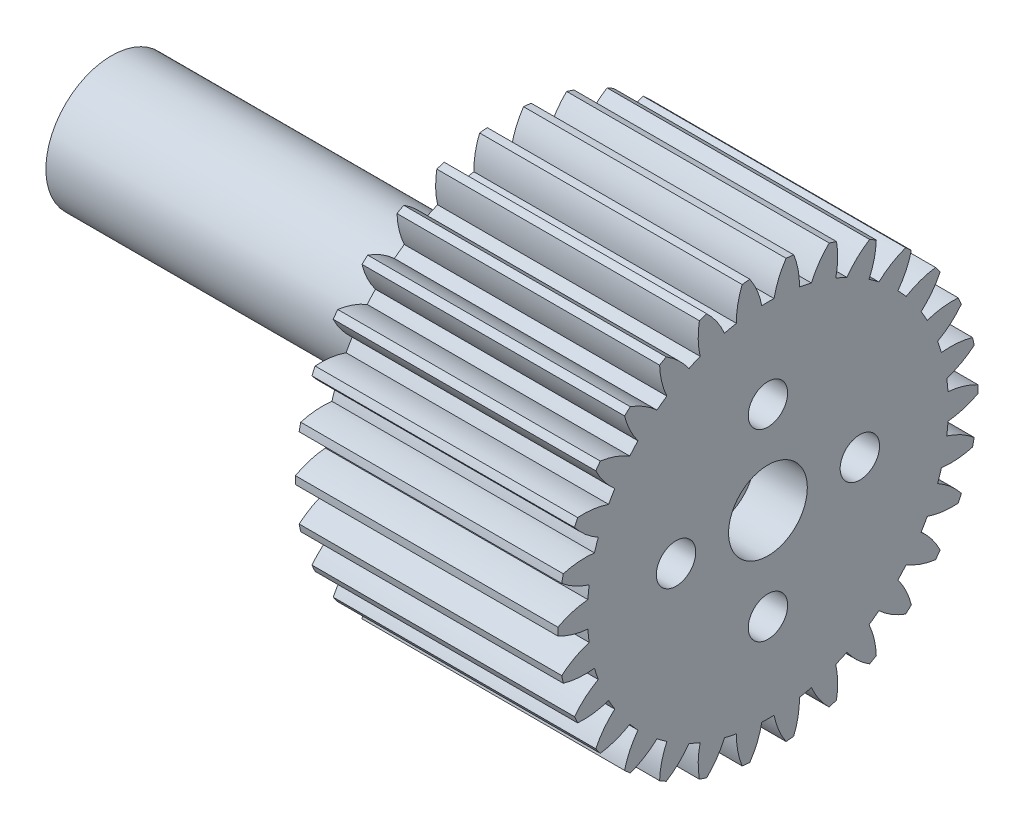
SolidWorks part; units mm, degrees
ref_plane "Plane1" through (0, 0, 0) normal (0, 0, 1) x (1, 0, 0)
ref_plane "Plane2" through (0, 0, 0) normal (0, 1, 0) x (1, 0, 0)
ref_plane "Plane3" through (0, 0, 0) normal (1, 0, 0) x (0, 0, -1)
sketch "HoldingSke" plane through (0, 0, 0) normal (0, 1, 0) x (1, 0, 0)
  line L0 (0, 0) -> (0.866, -0.5)
  line L1 (-15, 0) -> (100, 0) construction
  line L2 (0, 0) -> (-2.1039, 2.3779)
  line L3 (0, 0) -> (-11.863, 4.5341)
  line L4 (0, 0) -> (7.479, 4.318)
  line L5 (0, 0) -> (-46.8476, -17.4728)
  line L6 (0, 0) -> (-16.5793, -11.1861)
  line L7 (-2.1039, 2.3779) -> (8.6586, 51.2059)
  line L8 (-76.2, 54.61) -> (-76.1, 54.61)
  line L9 (-71.009, 38.7566) -> (-53.1078, 45.2721)
  line L10 (-76.2, 71.12) -> (104.1128, 71.12)
  line L11 (0, 0) -> (-20, 0)
  line L12 (-76.2, 101.6) -> (-76.162, 101.6)
  line L13 (24.9733, 27.94) -> (52.9518, 28.4284)
  line L14 (24.9733, 27.94) -> (24.9743, 27.94)
  line L15 (24.9733, 27.94) -> (100.4006, 29.5858)
  line L16 (-63.627, -1) -> (-12.827, -1)
  circle A0 centre (0, 0) radius 0.4
  circle A1 centre (0, 0) radius 13.749
  circle A2 centre (0, 0) radius 37.5
  circle A3 centre (0, 0) radius 0.4
  dimension "MHD" = 27.498
  dimension "Hub_dia" = 75
  dimension "Bore" = 0.8
  dimension "MBD" = 0.8
  dimension "Num_teeth" = 30
  dimension "Pitch" = 1
  dimension "Overall_len" = 50
  dimension "Show_teeth" = 30
  dimension "Thickness" = 20
  dimension "OAL" = 50.0001
  dimension "T_dim" = 0.1
  dimension "Ap" = 20
  dimension "H" = 19.05
  dimension "Pitch_radius" = 180.3128
  dimension "Width" = 20
  dimension "Backlash" = 0.038
  dimension "Addendum_fac" = 1
  dimension "Dedendum_fac" = 1.25
  dimension "Clearance_fac" = 0.25
  dimension "Dedendum_add" = 0.001
  dimension "Module" = 1
sketch "BasProSke" plane through (0, 0, 0) normal (0, 1, 0) x (1, 0, 0)
  line L0 (-10, 0) -> (60, 0) construction
  line L1 (0, 0) -> (0, 16)
  line L2 (0, 0) -> (20, 0)
  line L3 (20, 0) -> (20, 16)
  line L4 (20, 16) -> (0, 16)
  dimension "Thickness" = 20
  dimension "Diameter" = 32
revolve "Base-Revolve" add sketch "BasProSke" angle 360 about L0
sketch "TooCutSke" plane through (0, 0, 0) normal (1, 0, 0) x (0, 0, -1)
  line L1 (0, 0) -> (0, 107) construction
  line L2 (0, 0) -> (-0.8515, 14.9758) construction
  line L3 (0, 0) -> (-3.1323, 29.8014) construction
  line L4 (-0.8515, 14.9758) -> (-1.5661, 14.9007) construction
  arc A0 (0.4664, 13.7411) -> (-0.4664, 13.7411) centre (0, 0) ccw
  arc A1 (1.3975, 15.9644) -> (-1.3975, 15.9644) centre (0, 0) ccw
  circle A2 centre (0, 0) radius 15 construction
  circle A3 centre (0, 0) radius 14.0954 construction
  arc A4 (-0.4664, 13.7411) -> (-1.3975, 15.9644) centre (-6.3534, 12.5823) ccw
  arc A5 (1.3975, 15.9644) -> (0.4664, 13.7411) centre (6.3534, 12.5823) ccw
  dimension "Root_dia" = 27.498
  dimension "Overcut_dia" = 32.0508
  dimension "Pitch_dia" = 30
  dimension "Base_dia" = 28.1908
  dimension "Flank_rad" = 6
  dimension "Half_ang" = 6
  dimension "Half_CT" = 0.7185
extrude "ToothCut" cut sketch "TooCutSke" along normal through all
fillet "Breaks" [suppressed] radius 0.02
fillet "RootFillets" [suppressed] radius 0.251
pattern_circular "TeethCuts" count 30 every 12 about axis through (-10, 0, 0) along (1, 0, 0) of "ToothCut", "RootFillets", "Breaks"
sketch "HubNeaOneSke" plane through (0, 0, 0) normal (-1, 0, 0) x (0, 0, 1)
  circle A0 centre (0, 0) radius 13.749
  dimension "Diameter" = 27.498
extrude "HubNearOne" [suppressed] add sketch "HubNeaOneSke" along normal blind 30.0001
sketch "HubNeaBotSke" plane through (0, 0, 0) normal (-1, 0, 0) x (0, 0, 1)
  circle A0 centre (0, 0) radius 13.749
  dimension "Diameter" = 27.498
extrude "HubNearBoth" [suppressed] add sketch "HubNeaBotSke" along normal blind 15
ref_plane "FarPln" through (20, 0, 0) normal (1, 0, 0) x (0, 0, -1)
sketch "HubFarSke" plane through (20, 0, 0) normal (1, 0, 0) x (0, 0, -1)
  circle A0 centre (0, 0) radius 13.749
  dimension "Diameter" = 27.498
extrude "HubFar" [suppressed] add sketch "HubFarSke" along normal blind 15
sketch "BorSke" plane through (0, 0, 0) normal (1, 0, 0) x (0, 0, -1)
  circle A0 centre (0, 0) radius 0.4
  dimension "Diameter" = 0.8
extrude "Bore" cut sketch "BorSke" along normal mid plane 100.0001
sketch "KeySke" plane through (0, 0, 0) normal (1, 0, 0) x (0, 0, -1)
  line L0 (-0.05, 0) -> (-0.05, 0.5)
  line L1 (-0.05, 0.5) -> (0.05, 0.5)
  line L2 (0.05, 0.5) -> (0.05, 0)
  line L3 (0, 0) -> (0, 34) construction
  line L4 (-0.05, 0) -> (0.05, 0)
  dimension "Offset" = 0.5
  dimension "Width" = 0.1
extrude "Keyway" [suppressed] cut sketch "KeySke" along normal mid plane 100.0001
pattern_circular "Keyway2" [suppressed] count 2 every 90 about axis through (-10, 0, 0) along (1, 0, 0)
sketch "草图1" plane through (20, 0, 0) normal (1, 0, 0) x (0, 0, -1)
  line L0 (0, 0) -> (7, 0)
  line L1 (0, 0) -> (-7, 0)
  line L2 (0, 0) -> (0, 7)
  line L3 (0, 0) -> (0, -7)
  circle A0 centre (0, 0) radius 3
sketch "草图2" plane through (20, 0, 0) normal (1, 0, 0) x (0, 0, -1)
  circle A0 centre (0, 0) radius 5
extrude "凸台-拉伸1" add sketch "草图2" against normal blind 50
sketch "草图3" plane through (20, 0, 0) normal (1, 0, 0) x (0, 0, -1)
  circle A0 centre (0, 7) radius 1.5
  circle A1 centre (7, 0) radius 1.5
  circle A2 centre (0, -7) radius 1.5
  circle A3 centre (-7, 0) radius 1.5
extrude "切除-拉伸1" cut sketch "草图3" against normal up to next
extrude "切除-拉伸2" cut sketch "草图1" against normal blind 4 contours L2 A0 L1 | L0 A0 L2 | L1 A0 L3 | L3 A0 L0
hole_wizard "M6 螺纹孔1" positions "草图5" profile "草图6" tap size "M6" standard "GB"
sketch "草图5" plane through (-30, 0, 0) normal (-1, 0, 0) x (0, 0, 1)
  point P0 (0, 0)
sketch "草图6" plane through (-30, 0, 0) normal (0, 1, 0) x (0, 0, 1)
  line L0 (0, 0) -> (0, 16.5022)
  line L1 (0, 16.5022) -> (2.5, 15)
  line L2 (2.5, 15) -> (2.5, 0)
  line L5 (2.5, 0) -> (0, 0)
  line L10 (0, 16.5022) -> (-2.5, 15) construction
  line L11 (0, -6.35) -> (0, 107.95) construction
  dimension "螺纹孔钻头直径" = 5
  dimension "螺纹孔钻头深度" = 15
  dimension "导头角度" = 118
cosmetic thread "孔螺蚊线1" parameters "D1"=12, "D2"=6
equation "' \"Module@HoldingSke\" = 6.35"
equation "' \"Num_teeth@HoldingSke\" = 12"
equation "' \"Ap@HoldingSke\" =  20"
equation "' \"Ap@HoldingSke\" = 20"
equation "' \"Width@HoldingSke\" = 0.5 * 25.4"
equation "' \"Hub_dia@HoldingSke\"= 1 * 25.4"
equation "' \"Hub_dia@HoldingSke\" = 1 * 25.4"
equation "' \"Overall_len@HoldingSke\" = 1.0 * 25.4"
equation "' \"Bore@HoldingSke\" = 0.75 * 25.4"
equation "' \"T_dim@HoldingSke\" = 0.1 * 25.4"
equation "' \"Width@KeySke\" = 0.25 * 25.4"
equation "' \"Show_teeth@HoldingSke\" = 13"
equation "' \"Backlash@HoldingSke\" = 0.009 * 25.4"
equation "' \"Addendum_fac@HoldingSke\" = 1.0"
equation "' \"Dedendum_fac@HoldingSke\" = 1.25"
equation "' \"Dedendum_add@HoldingSke\" = 0.00005 * 25.4"
equation "' \"Clearance_fac@HoldingSke\" = 0.25"
equation "\"Pitch@HoldingSke\" = 1 / \"Module@HoldingSke\""
equation "\"Overcut_dia@TooCutSke\" = (\"Num_teeth@HoldingSke\" + 2 * \"Addendum_fac@HoldingSke\") / \"Pitch@HoldingSke\" + 0.002 * 25.4"
equation "\"Pitch_dia@TooCutSke\" = \"Num_teeth@HoldingSke\" / \"Pitch@HoldingSke\""
equation "\"Base_dia@TooCutSke\" = \"Num_teeth@HoldingSke\" / \"Pitch@HoldingSke\" * cos((\"Ap@HoldingSke\"  * 3.14159265 / 180))"
equation "\"Root_dia@TooCutSke\" = (\"Num_teeth@HoldingSke\" + 2) / \"Pitch@HoldingSke\" - 2 * (\"Addendum_fac@HoldingSke\" + \"Dedendum_fac@HoldingSke\") / \"Pitch@HoldingSke\" - \"Dedendum_add@HoldingSke\" * 2"
equation "\"Half_ang@TooCutSke\" = 180 / \"Num_teeth@HoldingSke\""
equation "\"Half_CT@TooCutSke\" = \"Num_teeth@HoldingSke\" / \"Pitch@HoldingSke\" * sin((3.14159265 / 2 / \"Num_teeth@HoldingSke\")) / 2 - 7 * \"Backlash@HoldingSke\" / 4"
equation "\"Flank_rad@TooCutSke\" = \"Num_teeth@HoldingSke\" / \"Pitch@HoldingSke\" / 5"
equation "\"Radius@RootFillets\" = \"Clearance_fac@HoldingSke\" / \"Pitch@HoldingSke\" + \"Dedendum_add@HoldingSke\""
equation "\"Break_rad@Breaks\" = 0.02 / \"Pitch@HoldingSke\""
equation "\"Thickness@HoldingSke\" = \"Width@HoldingSke\""
equation "\"OAL@HoldingSke\" = \"Thickness@HoldingSke\""
equation "\"MHD@HoldingSke\" = (\"Num_teeth@HoldingSke\" + 2) / \"Pitch@HoldingSke\" - 2 * (\"Addendum_fac@HoldingSke\" + \"Dedendum_fac@HoldingSke\")  / \"Pitch@HoldingSke\" - \"Dedendum_add@HoldingSke\" * 2"
equation "\"MBD@HoldingSke\" = (\"Num_teeth@HoldingSke\" + 2) / \"Pitch@HoldingSke\" - 2 * (\"Addendum_fac@HoldingSke\" + \"Dedendum_fac@HoldingSke\")  / \"Pitch@HoldingSke\" - \"Dedendum_add@HoldingSke\" * 2 - 0.002 * 25.4"
equation "\"MHD@HoldingSke\" = ((sgn( \"MHD@HoldingSke\" - \"Hub_dia@HoldingSke\" )-1)*( \"MHD@HoldingSke\" - \"Hub_dia@HoldingSke\" ))/-2+ \"Hub_dia@HoldingSke\""
equation "\"MBD@HoldingSke\" = ((sgn( \"MBD@HoldingSke\" - \"Bore@HoldingSke\" )-1)*( \"MBD@HoldingSke\" - \"Bore@HoldingSke\" ))/-2+ \"Bore@HoldingSke\""
equation "\"OAL@HoldingSke\" = ((sgn( \"OAL@HoldingSke\" - \"Overall_len@HoldingSke\" )+1)*( \"OAL@HoldingSke\" - \"Overall_len@HoldingSke\" ))/2 + \"Overall_len@HoldingSke\" + 0.000002 * 25.4"
equation "\"Num_teeth@TeethCuts\" = int( \"Show_teeth@HoldingSke\" ) + 1"
equation "\"Num_teeth@TeethCuts\" = ((sgn( \"Num_teeth@TeethCuts\" - \"Num_teeth@HoldingSke\" )-1)*( \"Num_teeth@TeethCuts\" - \"Num_teeth@HoldingSke\" ))/-2+ \"Num_teeth@HoldingSke\""
equation "\"Num_teeth@TeethCuts\" = ((sgn( \"Num_teeth@TeethCuts\" - 2.0)+1)*( \"Num_teeth@TeethCuts\" - 2.0))/2 +2.0"
equation "\"Angle@TeethCuts\" = 360.0 / \"Num_teeth@HoldingSke\""
equation "\"Diameter@BasProSke\" = (\"Num_teeth@HoldingSke\" + 2 * \"Addendum_fac@HoldingSke\") / \"Pitch@HoldingSke\""
equation "\"Thickness@BasProSke\"  = \"Thickness@HoldingSke\""
equation "' \"Fillet_rad@BasProSke\" =  \"Thickness@HoldingSke\" * 0.05"
equation "' \"Fillet_rad@BasProSke\" = \"Thickness@HoldingSke\" * 0.05"
equation "\"MHD@HoldingSke\" = ((sgn( \"MHD@HoldingSke\" - \"Root_dia@TooCutSke\" )-1)*( \"MHD@HoldingSke\" - \"Root_dia@TooCutSke\" ))/-2+ \"Root_dia@TooCutSke\""
equation "\"Diameter@HubNeaOneSke\" = \"MHD@HoldingSke\""
equation "\"Length@HubNearOne\" = \"OAL@HoldingSke\" - \"Thickness@BasProSke\""
equation "\"Diameter@HubNeaBotSke\" = \"MHD@HoldingSke\""
equation "\"Length@HubNearBoth\" = ( \"OAL@HoldingSke\" - \"Thickness@BasProSke\" ) / 2.0"
equation "\"Thickness@FarPln\" = \"Thickness@BasProSke\""
equation "\"Diameter@HubFarSke\" = \"MHD@HoldingSke\""
equation "\"Length@HubFar\" = ( \"OAL@HoldingSke\" - \"Thickness@BasProSke\" ) / 2.0"
equation "\"Diameter@BorSke\" = \"MBD@HoldingSke\""
equation "\"D1@Bore\" = \"OAL@HoldingSke\" * 2.0"
equation "\"D1@Keyway\" = \"OAL@HoldingSke\" * 2.0"
equation "\"Offset@KeySke\" = \"T_dim@HoldingSke\" + \"MBD@HoldingSke\" / 2.0"
